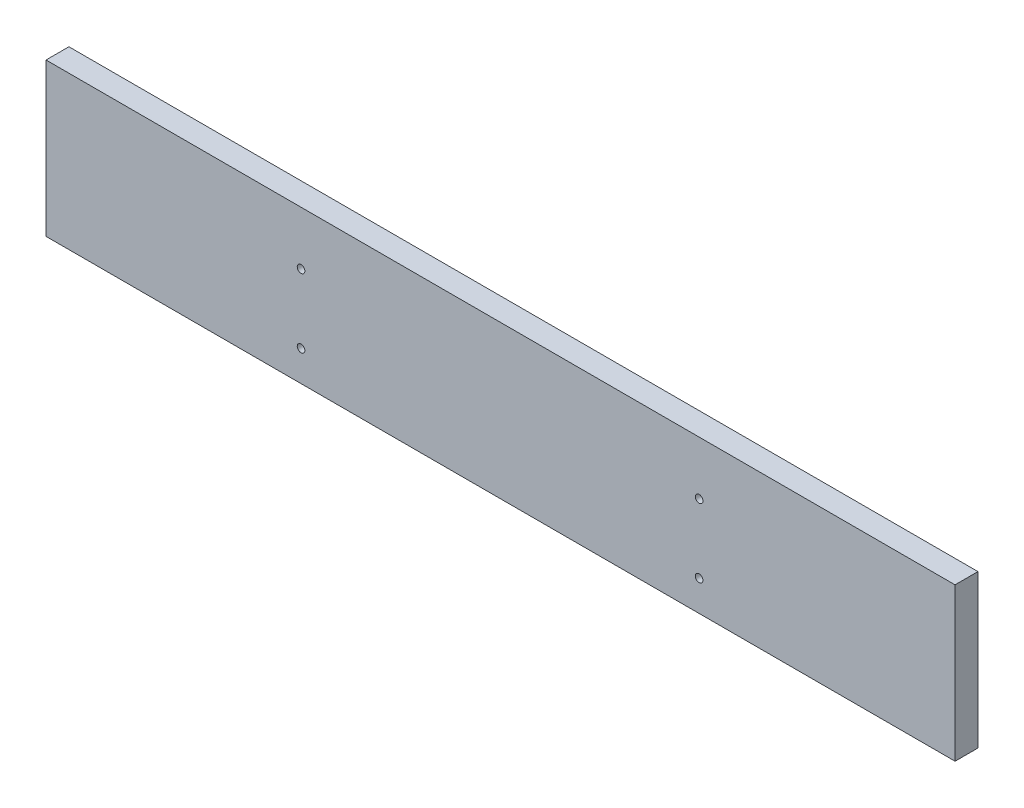
SolidWorks part; units mm, degrees
material "Pine"
ref_plane "Front Plane" through (0, 0, 0) normal (0, 0, 1) x (1, 0, 0)
ref_plane "Top Plane" through (0, 0, 0) normal (0, 1, 0) x (1, 0, 0)
ref_plane "Right Plane" through (0, 0, 0) normal (1, 0, 0) x (0, 0, -1)
sketch "Sketch1" plane through (0, 0, -348.1825) normal (0, 0, 1) x (1, 0, 0)
  line L1 (369.2728, 43.8334) -> (369.2728, 37.4834)
  line L2 (369.2728, 37.4834) -> (391.5386, 37.4834)
  line L4 (391.4978, 164.4834) -> (-364.1522, 164.4834)
  line L6 (-364.1522, 37.4834) -> (391.5386, 37.4834)
  line L7 (-364.1522, 164.4834) -> (-364.1522, 37.4834)
  line L8 (391.4978, 164.4834) -> (391.5386, 37.4834)
extrude "Boss-Extrude1" add sketch "Sketch1" along normal blind 19.05 contours L8 L4 L7 L6
hole_wizard "1/4 (0.25) Diameter Hole1" positions "Sketch4" profile "Sketch5" hole size "1/4" standard "ANSI Inch" end condition through all
sketch "Sketch4" plane through (0, 0, -329.1325) normal (0, 0, 1) x (1, 0, 0)
  point P0 (-152.139, 120.0334)
  point P3 (-152.139, 62.8834)
  point P6 (178.7728, 62.8834)
  point P9 (178.7728, 120.0334)
sketch "Sketch5" plane through (-152.139, 120.0334, -329.1325) normal (1, 0, 0) x (0, -1, 0)
  line L0 (0, 0) -> (0, 19.05)
  line L1 (0, 19.05) -> (3.175, 19.05)
  line L2 (3.175, 19.05) -> (3.175, 0)
  line L5 (3.175, 0) -> (0, 0)
  line L11 (0, -6.35) -> (0, 107.95) construction
  dimension "Thru Hole Dia." = 6.35
  dimension "Thru Hole Depth" = 19.05
